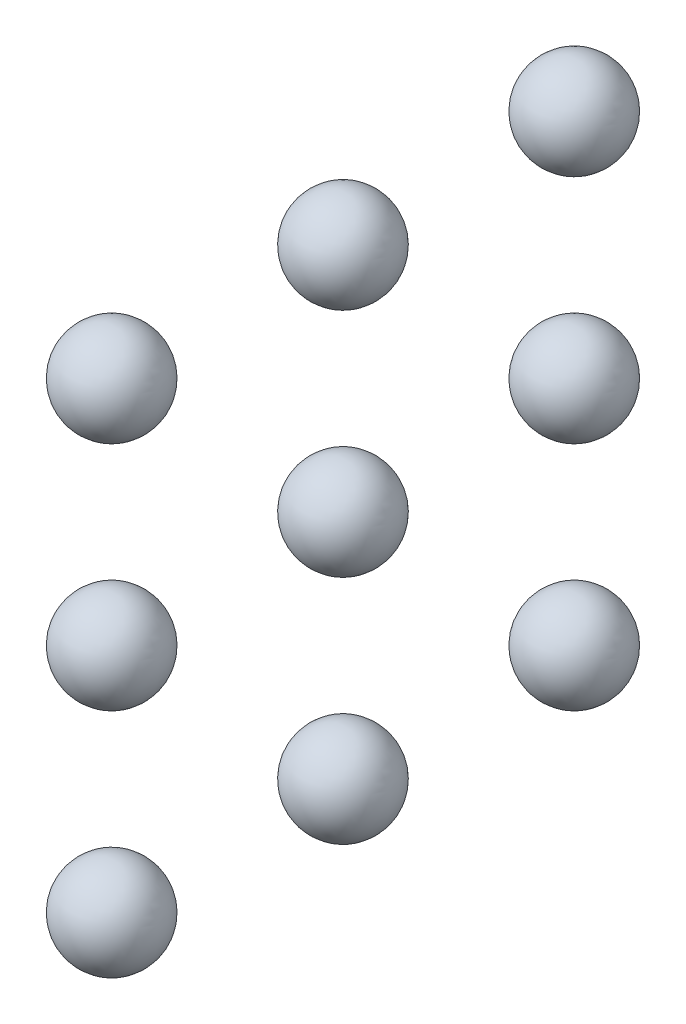
SolidWorks part; units mm, degrees
ref_plane "前视基准面" through (0, 0, 0) normal (0, 0, 1) x (1, 0, 0)
ref_plane "上视基准面" through (0, 0, 0) normal (0, 1, 0) x (1, 0, 0)
ref_plane "右视基准面" through (0, 0, 0) normal (1, 0, 0) x (0, 0, -1)
sketch "草图2" plane through (0, 0, 0) normal (0, 0, 1) x (1, 0, 0)
  line L0 (0, 3) -> (0, -3)
  arc A0 (0, 3) -> (0, -3) centre (0, 0) ccw
  dimension "D1" = 6
revolve "旋转5" add sketch "草图2" angle 360 about L0
pattern_linear "阵列(线性)3" count 3 spacing 15 along (0, 0, 1) count 3 spacing 15 along (0, 1, 0) of bodies 101
